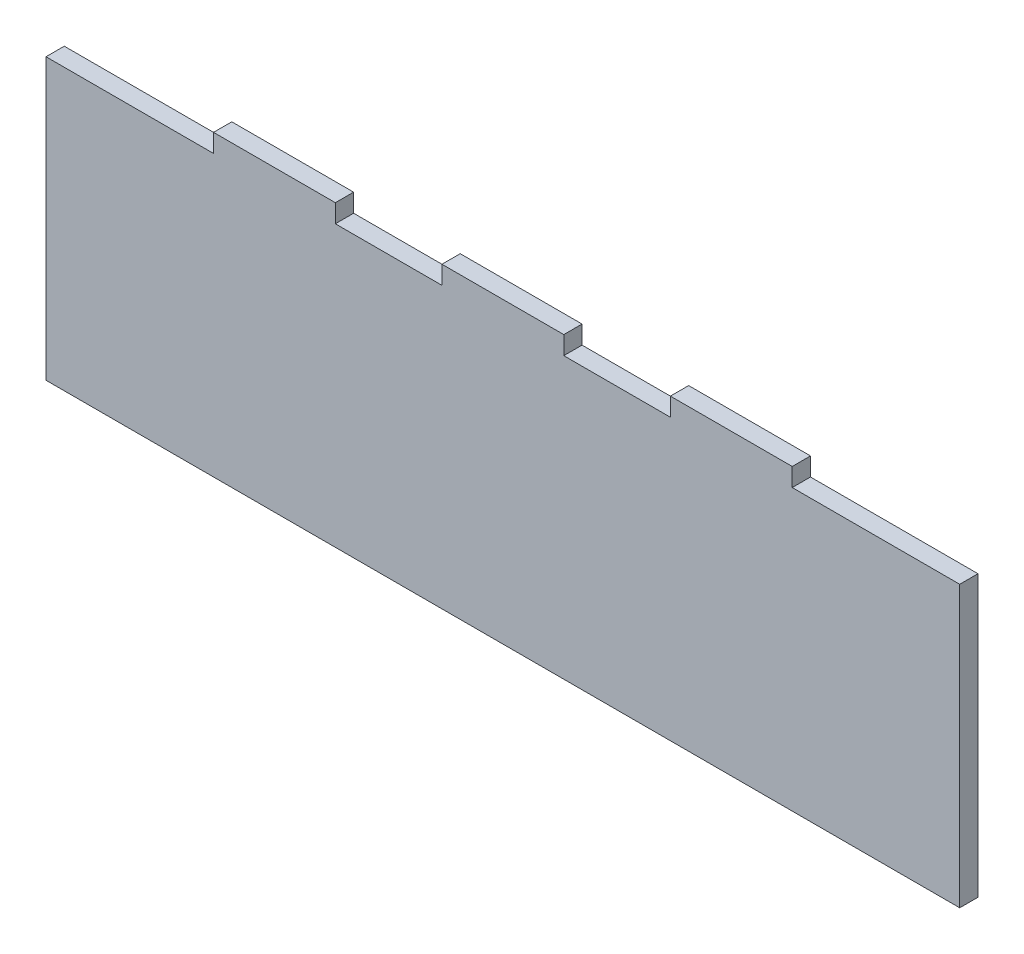
SolidWorks part; units mm, degrees
material "ABS"
ref_plane "Plan de face" through (0, 0, 0) normal (0, 0, 1) x (1, 0, 0)
ref_plane "Plan de dessus" through (0, 0, 0) normal (0, 1, 0) x (1, 0, 0)
ref_plane "Plan de droite" through (0, 0, 0) normal (1, 0, 0) x (0, 0, -1)
sketch "Esquisse1" plane through (0, 0, 0) normal (0, 0, 1) x (1, 0, 0)
  line L0 (0, -23) -> (0, 23) construction
  line L1 (75, -23) -> (-75, -23)
  line L2 (75, -23) -> (75, 23)
  line L3 (75, 23) -> (47.5, 23)
  line L4 (-75, -23) -> (-75, 23)
  line L5 (75, -23) -> (-75, 23) construction
  line L6 (75, 23) -> (-75, -23) construction
  line L23 (75, 23) -> (47.5, 23)
  line L27 (-37.5, -23) -> (-37.5, 23) construction
  line L28 (37.5, -23) -> (37.5, 23) construction
  line L29 (-47.5, 23) -> (-75, 23)
  line L34 (-27.5, 23) -> (-27.5, 26)
  line L35 (-27.5, 26) -> (-47.5, 26)
  line L36 (-47.5, 23) -> (-47.5, 26)
  line L37 (-27.5, 20) -> (-47.5, 26) construction
  line L38 (-27.5, 26) -> (-47.5, 20) construction
  line L40 (10, 23) -> (10, 26)
  line L41 (10, 26) -> (-10, 26)
  line L43 (-10, 23) -> (-10, 26)
  line L44 (10, 20) -> (-10, 26) construction
  line L45 (10, 26) -> (-10, 20) construction
  line L47 (47.5, 23) -> (47.5, 26)
  line L48 (47.5, 26) -> (27.5, 26)
  line L49 (27.5, 23) -> (27.5, 26)
  line L50 (47.5, 20) -> (27.5, 26) construction
  line L51 (47.5, 26) -> (27.5, 20) construction
  line L52 (-10, 23) -> (-27.5, 23)
  line L53 (-10, 23) -> (-27.5, 23)
  line L54 (-47.5, 23) -> (-75, 23)
  line L55 (27.5, 23) -> (10, 23)
  line L56 (27.5, 23) -> (0, 23)
  point P0 (0, 0)
  dimension "D1" = 150
  dimension "D2" = 46
  dimension "D3" = 37.5
  dimension "D4" = 37.5
  dimension "D5" = 6
  dimension "D6" = 20
extrude "Boss.-Extru.1" add sketch "Esquisse1" along normal blind 3
